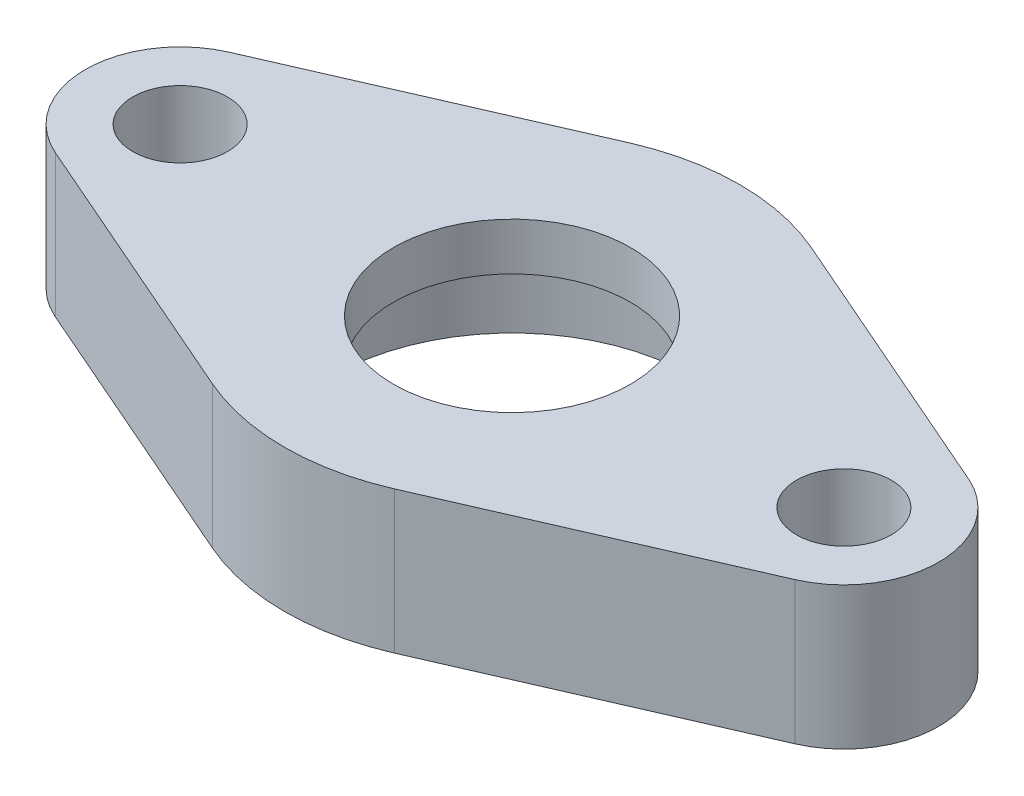
SolidWorks part; units mm, degrees
ref_plane "Front Plane" through (0, 0, 0) normal (0, 0, 1) x (1, 0, 0)
ref_plane "Top Plane" through (0, 0, 0) normal (0, 1, 0) x (1, 0, 0)
ref_plane "Right Plane" through (0, 0, 0) normal (1, 0, 0) x (0, 0, -1)
sketch "Sketch1" plane through (0, 0, 0) normal (0, 1, 0) x (1, 0, 0)
  line L0 (-3.84, 8.7985) -> (-15.6, 3.6661)
  line L1 (-15.6, -3.6661) -> (-3.84, -8.7985)
  line L2 (0, 0) -> (0, -7.6) construction
  line L3 (3.84, 8.7985) -> (15.6, 3.6661)
  line L4 (15.6, -3.6661) -> (3.84, -8.7985)
  circle A0 centre (0, 0) radius 7.6
  circle A1 centre (0, 0) radius 9.6
  arc A2 (-15.6, 3.6661) -> (-15.6, -3.6661) centre (-14, 0) ccw
  circle A3 centre (-14, 0) radius 2
  circle A4 centre (14, 0) radius 2
  arc A5 (15.6, 3.6661) -> (15.6, -3.6661) centre (14, 0) cw
  dimension "D1" = 15.2
  dimension "D3" = 4
  dimension "D4" = 4
  dimension "D5" = 14
  dimension "D2" = 2
extrude "Boss-Extrude1" add sketch "Sketch1" along normal blind 4 contours L0 A2 L1 A1 A3 | A1 A0 | A5 L3 A1 L4 A4
sketch "Sketch2" plane through (0, 4, 0) normal (0, 1, 0) x (1, 0, 0)
  line L4 (-3.84, 8.7985) -> (-15.6, 3.6661)
  line L5 (-15.6, -3.6661) -> (-3.84, -8.7985)
  line L6 (3.84, -8.7985) -> (15.6, -3.6661)
  line L7 (15.6, 3.6661) -> (3.84, 8.7985)
  line L8 (-3.84, 8.7985) -> (-15.6, 3.6661)
  line L9 (-15.6, -3.6661) -> (-3.84, -8.7985)
  line L10 (3.84, -8.7985) -> (15.6, -3.6661)
  line L11 (15.6, 3.6661) -> (3.84, 8.7985)
  circle A0 centre (0, 0) radius 5
  circle A1 centre (-14, 0) radius 2
  circle A2 centre (-14, 0) radius 2
  circle A3 centre (14, 0) radius 2
  circle A4 centre (14, 0) radius 2
  arc A8 (-15.6, 3.6661) -> (-15.6, -3.6661) centre (-14, 0) ccw
  arc A9 (-3.84, -8.7985) -> (3.84, -8.7985) centre (0, 0) ccw
  arc A10 (15.6, -3.6661) -> (15.6, 3.6661) centre (14, 0) ccw
  arc A11 (3.84, 8.7985) -> (-3.84, 8.7985) centre (0, 0) ccw
  arc A12 (-15.6, 3.6661) -> (-15.6, -3.6661) centre (-14, 0) ccw
  arc A13 (-3.84, -8.7985) -> (3.84, -8.7985) centre (0, 0) ccw
  arc A14 (15.6, -3.6661) -> (15.6, 3.6661) centre (14, 0) ccw
  arc A15 (3.84, 8.7985) -> (-3.84, 8.7985) centre (0, 0) ccw
  dimension "D4" = 10
  dimension "D1" = 0
  dimension "D2" = 0
  dimension "D3" = 0
extrude "Boss-Extrude2" add sketch "Sketch2" along normal blind 2
